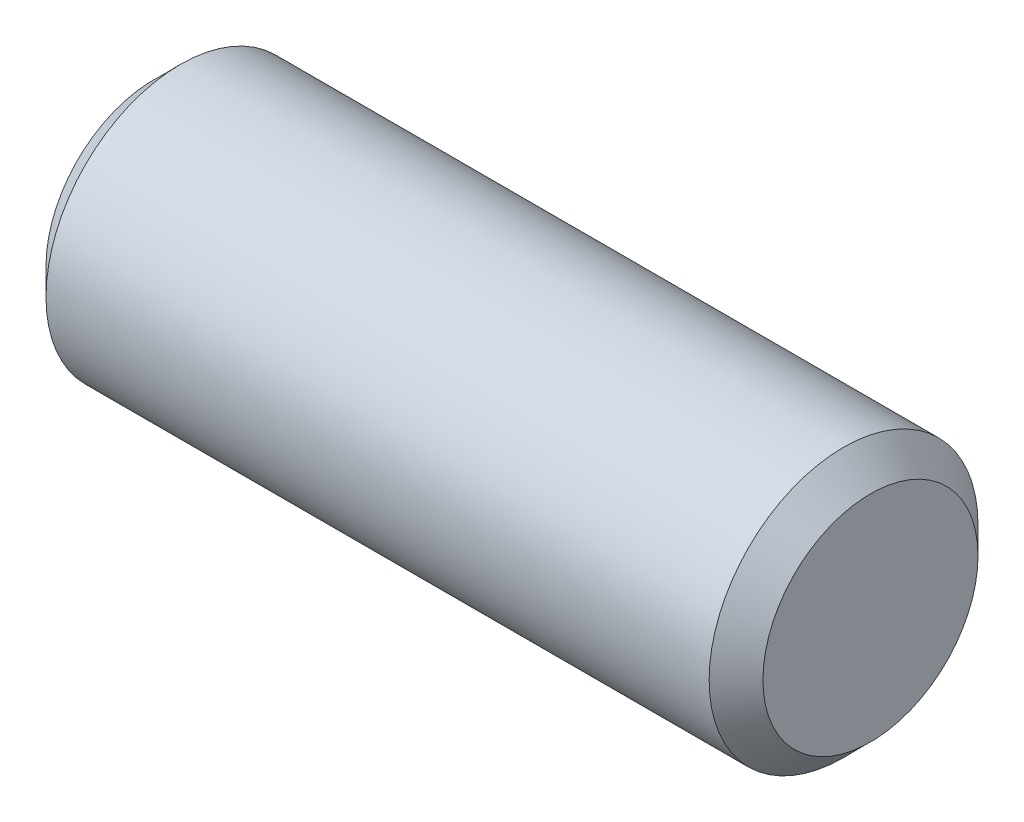
SolidWorks part; units mm, degrees
ref_plane "Front Plane" through (0, 0, 0) normal (0, 0, 1) x (1, 0, 0)
ref_plane "Top Plane" through (0, 0, 0) normal (0, 1, 0) x (1, 0, 0)
ref_plane "Right Plane" through (0, 0, 0) normal (1, 0, 0) x (0, 0, -1)
sketch "Sketch1" plane through (0, 0, 0) normal (0, 0, 1) x (1, 0, 0)
  line L0 (-25.4, 0) -> (25.4, 0) construction
  line L1 (-25.4, 9.525) -> (-25.4, -9.525) construction
  line L2 (25.4, 9.525) -> (25.4, -9.525) construction
  dimension "Diameter" = 19.05
  dimension "Length" = 50.8
sketch "Sketch2" plane through (0, 0, 0) normal (1, 0, 0) x (0, 0, -1)
  circle A0 centre (0, 0) radius 9.525
extrude "Extrude1" add sketch "Sketch2" against normal up to vertex (25.4 mm away) and the other way up to vertex (25.4 mm away) up to point (-25.4, 0, 0) other way up to point (25.4, 0, 0)
chamfer "Chamfer1" distance 1.905 angle 45 2 edges at (25.4, 0, -9.525) (-25.4, 0, -9.525)
equation "\"D1@Chamfer1\" = \"Diameter@Sketch1\"*.1"
